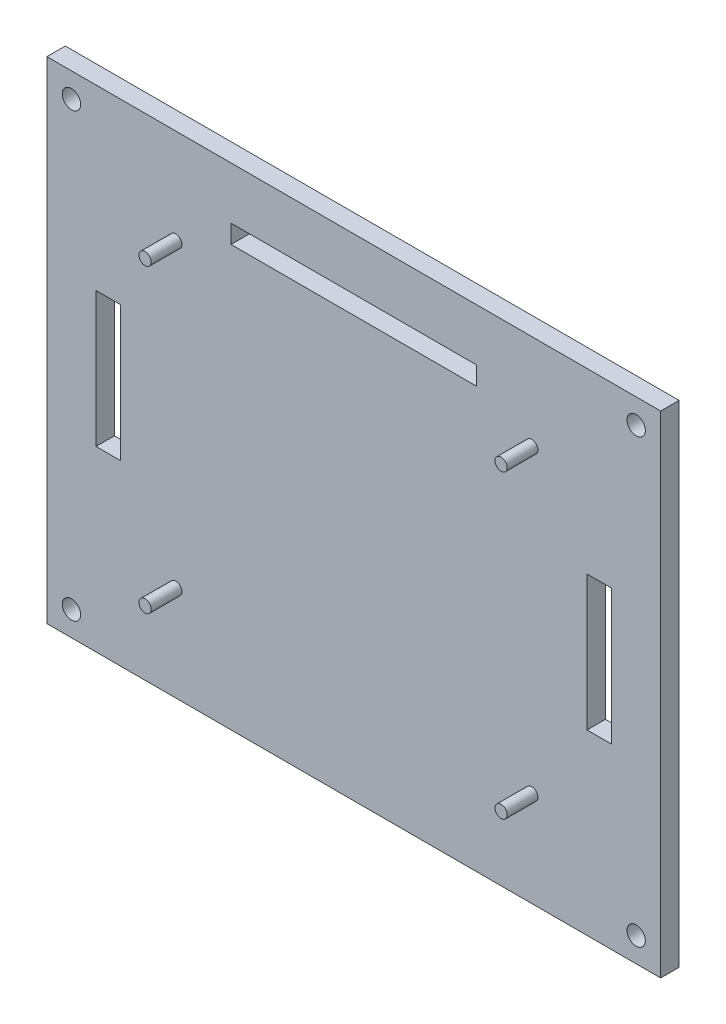
SolidWorks part; units mm, degrees
ref_plane "Plan de face" through (0, 0, 0) normal (0, 0, 1) x (1, 0, 0)
ref_plane "Plan de dessus" through (0, 0, 0) normal (0, 1, 0) x (1, 0, 0)
ref_plane "Plan de droite" through (0, 0, 0) normal (1, 0, 0) x (0, 0, -1)
sketch "Esquisse1" plane through (0, 0, 0) normal (0, 0, 1) x (1, 0, 0)
  line L0 (-46, 36) -> (46, 36) construction
  line L1 (50, -40) -> (-50, -40)
  line L2 (50, -40) -> (50, 40)
  line L3 (50, 40) -> (-50, 40)
  line L4 (-50, -40) -> (-50, 40)
  line L5 (50, -40) -> (-50, 40) construction
  line L6 (50, 40) -> (-50, -40) construction
  line L7 (-46, 36) -> (-46, -36) construction
  line L8 (0, -40) -> (0, 40) construction
  line L13 (-42, -11) -> (-38, -11)
  line L14 (46, 36) -> (46, -36) construction
  line L19 (42, -11) -> (38, -11)
  line L20 (20, 28.5) -> (-20, 28.5)
  line L21 (20, 28.5) -> (20, 31.5)
  line L22 (20, 31.5) -> (-20, 31.5)
  line L23 (-20, 28.5) -> (-20, 31.5)
  line L24 (20, 28.5) -> (-20, 31.5) construction
  line L25 (20, 31.5) -> (-20, 28.5) construction
  line L26 (42, -11) -> (42, 11)
  line L27 (42, 11) -> (38, 11)
  line L28 (38, -11) -> (38, 11)
  line L29 (42, -11) -> (38, 11) construction
  line L30 (42, 11) -> (38, -11) construction
  line L31 (-38, -11) -> (-38, 11)
  line L32 (-42, 11) -> (-38, 11)
  line L33 (-42, -11) -> (-42, 11)
  line L34 (40, 0) -> (46, 0) construction
  circle A0 centre (-46, 36) radius 1.5
  circle A1 centre (46, 36) radius 1.5
  circle A2 centre (46, -36) radius 1.5
  circle A3 centre (-46, -36) radius 1.5
  point P0 (0, 0)
  point P8 (-46, 0)
  point P24 (40, 0)
  point P26 (0, 30)
  dimension "D3" = 3
  dimension "D1" = 80
  dimension "D2" = 100
  dimension "D4" = 4
  dimension "D5" = 4
  dimension "D8" = 92
  dimension "D9" = 72
  dimension "D10" = 10
  dimension "D12" = 3
  dimension "D13" = 40
  dimension "D14" = 10
  dimension "D16" = 22
  dimension "D17" = 4
  dimension "D6" = 2
  dimension "D7" = 2
extrude "Boss.-Extru.1" add sketch "Esquisse1" along normal blind 3
sketch "Esquisse2" plane through (0, 0, 3) normal (0, 0, 1) x (1, 0, 0)
  line L0 (-50, 0) -> (50, 0) construction
  line L1 (-50, 40) -> (-50, -40) construction
  line L2 (50, -40) -> (50, 40) construction
  line L3 (0, 40) -> (0, -40) construction
  line L4 (50, 40) -> (-50, 40) construction
  line L5 (-50, -40) -> (50, -40) construction
  line L6 (-29, 24.5) -> (29, 24.5) construction
  circle A0 centre (-29, 24.5) radius 1
  circle A1 centre (29, 24.5) radius 1
  circle A2 centre (29, -24.5) radius 1
  circle A3 centre (-29, -24.5) radius 1
  dimension "D1" = 2
  dimension "D2" = 58
  dimension "D3" = 49
  dimension "D6" = 58
  dimension "D4" = 2
  dimension "D5" = 2
extrude "Boss.-Extru.2" add sketch "Esquisse2" along normal blind 5
